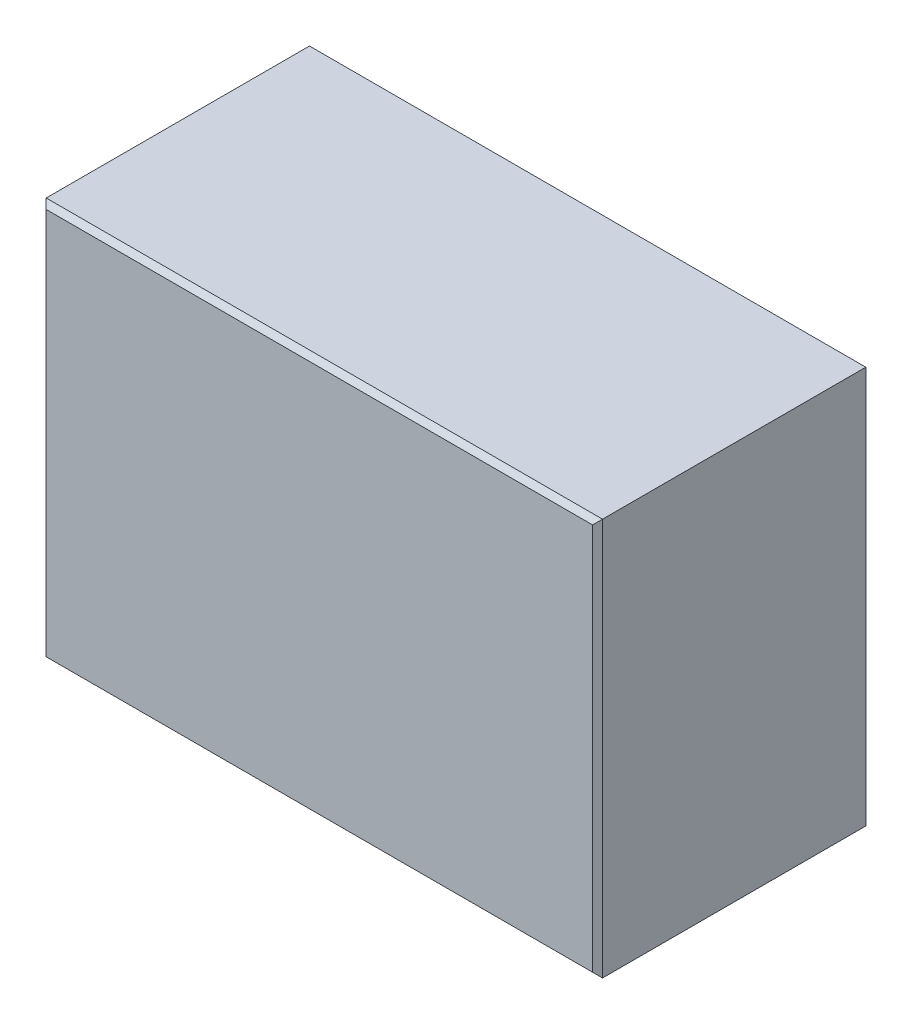
SolidWorks part; units mm, degrees
material "AISI 1020"
ref_plane "Face" through (0, 0, 0) normal (0, 0, 1) x (1, 0, 0)
ref_plane "Dessus" through (0, 0, 0) normal (0, 1, 0) x (1, 0, 0)
ref_plane "Droite" through (0, 0, 0) normal (1, 0, 0) x (0, 0, -1)
sketch "Esquisse1" plane through (0, 0, 0) normal (0, 0, 1) x (1, 0, 0)
  line L0 (-10, 0) -> (10, 0) construction
  line L1 (0, 10) -> (0, -10) construction
  line L3 (-5.6, 4) -> (5.6, 4)
  line L4 (-5.6, 4) -> (-5.6, -4)
  line L5 (-5.6, -4) -> (5.6, -4)
  line L6 (5.6, 4) -> (5.6, -4)
  dimension "D1" = 4
  dimension "D2" = 8
  dimension "D3" = 5.6
  dimension "D4" = 11.2
extrude "Boss.-Extru.1" add sketch "Esquisse1" along normal blind 5.5
chamfer "Chanfrein1" distance 0.1 angle 45 8 edges at (0, -4, 0) (5.6, 0, 0) (0, 4, 0) (-5.6, 0, 0) (0, 4, 5.5) (5.6, 0, 5.5) (0, -4, 5.5) (-5.6, 0, 5.5)
